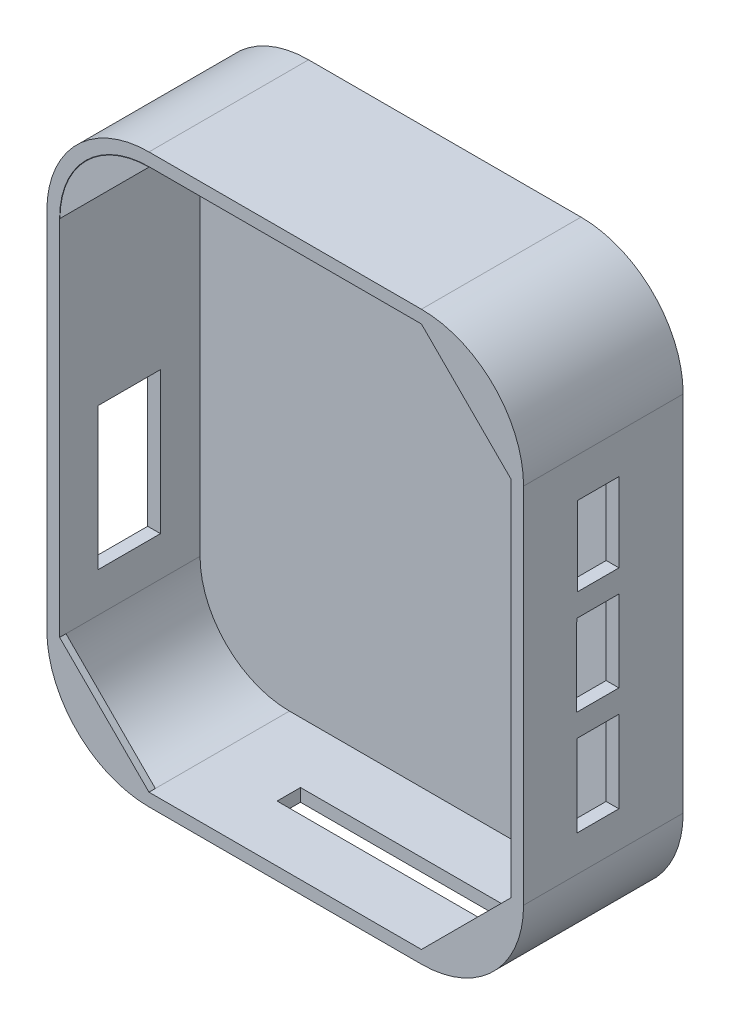
SolidWorks part; units mm, degrees
ref_plane "前视基准面" through (0, 0, 0) normal (0, 0, 1) x (1, 0, 0)
ref_plane "上视基准面" through (0, 0, 0) normal (0, 1, 0) x (1, 0, 0)
ref_plane "右视基准面" through (0, 0, 0) normal (1, 0, 0) x (0, 0, -1)
other "Configuration Table"
sketch "草图1" plane through (0, 0, 0) normal (0, 0, 1) x (1, 0, 0)
  line L1 (-10.67, 22.215) -> (10.67, 22.215)
  line L2 (-18.67, 14.215) -> (-18.67, -14.215)
  line L3 (-10.67, -22.215) -> (10.67, -22.215)
  line L4 (18.67, 14.215) -> (18.67, -14.215)
  line L5 (0, -22.215) -> (0, 22.215) construction
  line L6 (-18.67, 0) -> (18.67, 0) construction
  arc A0 (10.67, -22.215) -> (18.67, -14.215) centre (10.67, -14.215) ccw
  arc A1 (-18.67, -14.215) -> (-10.67, -22.215) centre (-10.67, -14.215) ccw
  arc A2 (10.67, 22.215) -> (18.67, 14.215) centre (10.67, 14.215) cw
  arc A3 (-10.67, 22.215) -> (-18.67, 14.215) centre (-10.67, 14.215) ccw
  point P0 (0, 0)
  point P8 (-18.67, -22.215)
  point P11 (18.67, 22.215)
  point P15 (-18.67, 22.215)
  dimension "D3" = 8
  dimension "D1" = 37.34
  dimension "D2" = 44.43
extrude "凸台-拉伸2" add sketch "草图1" along normal blind 1.5
sketch "草图4" plane through (0, 0, 1.5) normal (0, 0, 1) x (1, 0, 0)
  line L0 (17.67, -14.215) -> (17.67, 14.215)
  line L1 (10.67, 21.215) -> (-10.67, 21.215)
  line L2 (-17.67, 14.215) -> (-17.67, -14.215)
  line L3 (-10.67, -21.215) -> (10.67, -21.215)
  line L4 (18.67, -14.215) -> (18.67, 14.215)
  line L5 (10.67, 22.215) -> (-10.67, 22.215)
  line L6 (-18.67, 14.215) -> (-18.67, -14.215)
  line L7 (-10.67, -22.215) -> (10.67, -22.215)
  line L8 (18.67, -14.215) -> (18.67, 14.215)
  line L9 (10.67, 22.215) -> (-10.67, 22.215)
  line L10 (-18.67, 14.215) -> (-18.67, -14.215)
  line L11 (-10.67, -22.215) -> (10.67, -22.215)
  arc A0 (10.67, -21.215) -> (17.67, -14.215) centre (10.67, -14.215) ccw
  arc A1 (17.67, 14.215) -> (10.67, 21.215) centre (10.67, 14.215) ccw
  arc A2 (-10.67, 21.215) -> (-17.67, 14.215) centre (-10.67, 14.215) ccw
  arc A3 (-17.67, -14.215) -> (-10.67, -21.215) centre (-10.67, -14.215) ccw
  arc A4 (10.67, -22.215) -> (18.67, -14.215) centre (10.67, -14.215) ccw
  arc A5 (18.67, 14.215) -> (10.67, 22.215) centre (10.67, 14.215) ccw
  arc A6 (-10.67, 22.215) -> (-18.67, 14.215) centre (-10.67, 14.215) ccw
  arc A7 (-18.67, -14.215) -> (-10.67, -22.215) centre (-10.67, -14.215) ccw
  arc A8 (10.67, -22.215) -> (18.67, -14.215) centre (10.67, -14.215) ccw
  arc A9 (18.67, 14.215) -> (10.67, 22.215) centre (10.67, 14.215) ccw
  arc A10 (-10.67, 22.215) -> (-18.67, 14.215) centre (-10.67, 14.215) ccw
  arc A11 (-18.67, -14.215) -> (-10.67, -22.215) centre (-10.67, -14.215) ccw
  dimension "D1" = 0
  dimension "D2" = 1
extrude "凸台-拉伸4" add sketch "草图4" along normal blind 11
sketch "草图5" plane through (0, 0, 12.5) normal (0, 0, 1) x (1, 0, 0)
  line L0 (-10.67, 21.1858) -> (-17.6408, 14.215)
  arc A0 (-17.6408, 14.215) -> (-10.67, 21.1858) centre (-10.67, 14.215) cw
  arc A2 (-17.6408, 14.215) -> (-17.6389, 14.3807) centre (-10.67, 14.215) cw
extrude "凸台-拉伸6" add sketch "草图5" against normal blind 0.5 separate body contours A0 L0
sketch "草图8" plane through (0, 0, 12.5) normal (0, 0, 1) x (1, 0, 0)
  line L0 (-17.67, -14.215) -> (-10.67, -21.215)
  arc A0 (-10.67, -21.215) -> (-17.67, -14.215) centre (-10.67, -14.215) cw
  arc A1 (-17.67, -14.215) -> (-10.67, -21.215) centre (-10.67, -14.215) ccw construction
extrude "凸台-拉伸7" add sketch "草图8" against normal blind 0.5 contours L0 A0
sketch "草图9" plane through (0, 0, 12.5) normal (0, 0, 1) x (1, 0, 0)
  line L0 (10.67, 21.215) -> (17.67, 14.215)
  line L1 (10.67, -21.215) -> (17.67, -14.215)
  arc A0 (17.67, -14.215) -> (10.67, -21.215) centre (10.67, -14.215) cw
  arc A1 (10.67, -21.215) -> (17.67, -14.215) centre (10.67, -14.215) ccw construction
  arc A2 (10.67, 21.215) -> (17.67, 14.215) centre (10.67, 14.215) cw
  arc A4 (17.67, 14.215) -> (10.67, 21.215) centre (10.67, 14.215) ccw construction
extrude "凸台-拉伸8" add sketch "草图9" against normal blind 0.5 contours L0 A2
sketch "草图10" plane through (0, 0, 12.5) normal (0, 0, 1) x (1, 0, 0)
  line L0 (17.67, -14.215) -> (10.67, -21.215)
  arc A0 (17.67, -14.215) -> (10.67, -21.215) centre (10.67, -14.215) cw
  arc A1 (10.67, -21.215) -> (17.67, -14.215) centre (10.67, -14.215) ccw construction
extrude "凸台-拉伸9" add sketch "草图10" against normal blind 0.5
sketch "草图12" plane through (-18.67, 0, 0) normal (-1, 0, 0) x (0, 0, 1)
  line L1 (4.6019, 0) -> (9.4996, 0)
  line L2 (4.6019, 0) -> (4.6019, -11.1278)
  line L3 (4.6019, -11.1278) -> (9.4996, -11.1278)
  line L4 (9.4996, 0) -> (9.4996, -11.1278)
extrude "切除-拉伸3" cut sketch "草图12" against normal blind 3
sketch "草图13" plane through (18.67, 0, 0) normal (1, 0, 0) x (0, 0, -1)
  line L1 (-8.2672, 11.1278) -> (-5.026, 11.1278)
  line L2 (-8.2672, 11.1278) -> (-8.2672, 4.9337)
  line L3 (-8.2672, 4.9337) -> (-5.026, 4.9337)
  line L4 (-5.026, 11.1278) -> (-5.026, 4.9337)
extrude "切除-拉伸4" cut sketch "草图13" against normal blind 3
sketch "草图14" plane through (18.67, 0, 0) normal (1, 0, 0) x (0, 0, -1)
  line L1 (-8.3475, 2.917) -> (-5.0344, 2.917)
  line L2 (-8.3475, 2.917) -> (-8.3475, -3.2051)
  line L3 (-8.3475, -3.2051) -> (-5.0344, -3.2051)
  line L4 (-5.0344, 2.917) -> (-5.0344, -3.2051)
extrude "切除-拉伸5" cut sketch "草图14" against normal blind 3
sketch "草图15" plane through (18.67, 0, 0) normal (1, 0, 0) x (0, 0, -1)
  line L1 (-8.1054, -5.0777) -> (-5.2244, -5.0777)
  line L2 (-8.1054, -5.0777) -> (-8.1054, -11.3439)
  line L3 (-8.1054, -11.3439) -> (-5.2244, -11.3439)
  line L4 (-5.2244, -5.0777) -> (-5.2244, -11.3439)
extrude "切除-拉伸6" cut sketch "草图15" against normal blind 3
sketch "草图16" plane through (0, -22.215, 0) normal (0, -1, 0) x (1, 0, 0)
  line L0 (10.67, 12.5) -> (10.67, 0) construction
  line L14 (-5.0516, 8.0862) -> (10.67, 8.0862)
  line L15 (-5.0516, 8.0862) -> (-5.0516, 6.25)
  line L16 (-5.0516, 6.25) -> (10.67, 6.25)
  line L17 (10.67, 8.0862) -> (10.67, 6.25)
extrude "切除-拉伸7" cut sketch "草图16" against normal blind 3
sketch "草图19" plane through (18.67, 0, 0) normal (1, 0, 0) x (0, 0, -1)
  line L14 (-8.3096, 3.1663) -> (-5.0344, 3.1663)
  line L15 (-8.3096, 3.1663) -> (-8.3096, -3.2051)
  line L16 (-8.3096, -3.2051) -> (-5.0344, -3.2051)
  line L17 (-5.0344, 3.1663) -> (-5.0344, -3.2051)
  line L19 (-8.3096, -4.9929) -> (-5.0344, -4.9929)
  line L20 (-8.3096, -4.9929) -> (-8.3096, -11.4072)
  line L21 (-8.3096, -11.4072) -> (-5.0344, -11.4072)
  line L22 (-5.0344, -4.9929) -> (-5.0344, -11.4072)
extrude "切除-拉伸10" cut sketch "草图19" against normal blind 3
